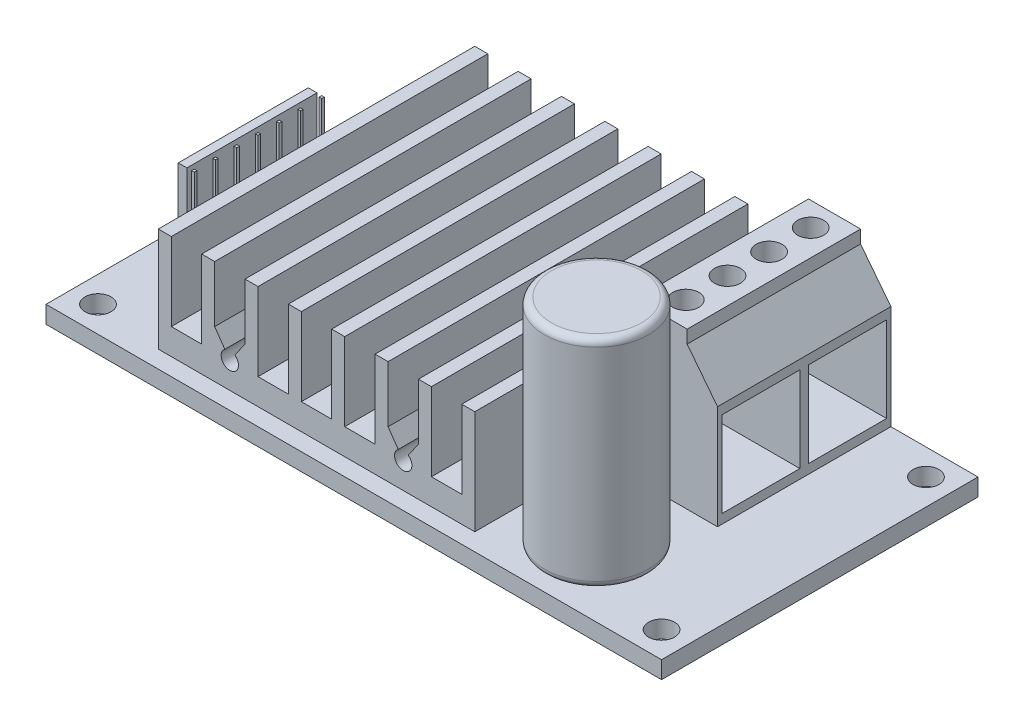
SolidWorks part; units mm, degrees
ref_plane "Front Plane" through (0, 0, 0) normal (0, 0, 1) x (1, 0, 0)
ref_plane "Top Plane" through (0, 0, 0) normal (0, 1, 0) x (1, 0, 0)
ref_plane "Right Plane" through (0, 0, 0) normal (1, 0, 0) x (0, 0, -1)
sketch "Sketch1" plane through (0, 0, 0) normal (0, 1, 0) x (1, 0, 0)
  line L1 (-35.5, -18.25) -> (35.5, -18.25)
  line L2 (-35.5, -18.25) -> (-35.5, 18.25)
  line L3 (-35.5, 18.25) -> (35.5, 18.25)
  line L4 (35.5, -18.25) -> (35.5, 18.25)
  line L5 (-35.5, -18.25) -> (35.5, 18.25) construction
  line L6 (-35.5, 18.25) -> (35.5, -18.25) construction
  point P0 (0, 0)
  dimension "D1" = 71
  dimension "D2" = 36.5
extrude "Board" add sketch "Sketch1" along normal blind 2
sketch "Sketch2" plane through (0, 2, 0) normal (0, 1, 0) x (1, 0, 0)
  line L0 (35.5, 18.25) -> (-35.5, 18.25) construction
  line L1 (-35.5, 18.25) -> (-35.5, -18.25) construction
  line L2 (-35.5, 0) -> (0, 0) construction
  line L3 (0, 0) -> (0, 18.25) construction
  circle A0 centre (-32.5, 15.25) radius 1.5
  circle A1 centre (32.5, 15.25) radius 1.5
  circle A2 centre (32.5, -15.25) radius 1.5
  circle A3 centre (-32.5, -15.25) radius 1.5
  dimension "D1" = 3
  dimension "D2" = 3
  dimension "D3" = 3
extrude "Screw Holes" cut sketch "Sketch2" against normal blind 2
sketch "Sketch3" plane through (0, 0, 18.25) normal (0, 0, 1) x (1, 0, 0)
  line L0 (-35.5, 2) -> (-23.5, 2) construction
  line L1 (-35.5, 2) -> (35.5, 2) construction
  line L2 (-22.5449, 4) -> (13.9551, 4)
  line L3 (-22.5449, 4) -> (-22.5449, 16)
  line L4 (-17.5449, 7) -> (-17.5449, 16)
  line L5 (-12.5449, 9.4993) -> (-12.5449, 16)
  line L6 (-7.5449, 7) -> (-7.5449, 16)
  line L7 (-2.5449, 7) -> (-2.5449, 16)
  line L8 (2.4551, 7) -> (2.4551, 16)
  line L9 (7.4551, 9.4993) -> (7.4551, 16)
  line L10 (12.4551, 7) -> (12.4551, 16)
  line L11 (-21.0449, 7) -> (-21.0449, 16)
  line L12 (-16.0449, 9.4993) -> (-16.0449, 16)
  line L13 (-11.0449, 7) -> (-11.0449, 16)
  line L14 (-6.0449, 7) -> (-6.0449, 16)
  line L15 (-1.0449, 7) -> (-1.0449, 16)
  line L16 (3.9551, 9.4993) -> (3.9551, 16)
  line L17 (8.9551, 7) -> (8.9551, 16)
  line L18 (13.9551, 4) -> (13.9551, 16)
  line L19 (-22.5449, 16) -> (-21.0449, 16)
  line L20 (-17.5449, 16) -> (-16.0449, 16)
  line L21 (-12.5449, 16) -> (-11.0449, 16)
  line L22 (-7.5449, 16) -> (-6.0449, 16)
  line L23 (-2.5449, 16) -> (-1.0449, 16)
  line L24 (2.4551, 16) -> (3.9551, 16)
  line L25 (7.4551, 16) -> (8.9551, 16)
  line L26 (12.4551, 16) -> (13.9551, 16)
  line L27 (-21.0449, 7) -> (-17.5449, 7)
  line L28 (-22.5449, 7) -> (13.9551, 7) construction
  line L29 (-21.0449, 4) -> (-21.0449, 16) construction
  line L30 (8.9551, 7) -> (12.4551, 7)
  line L32 (-1.0449, 7) -> (2.4551, 7)
  line L33 (-6.0449, 7) -> (-2.5449, 7)
  line L34 (-11.0449, 7) -> (-7.5449, 7)
  line L35 (-13.5823, 7) -> (-15.0075, 7)
  line L36 (-14.2949, 7) -> (-14.2949, 8) construction
  line L37 (-13.7213, 7.8192) -> (-12.5449, 9.4993)
  line L38 (-14.8685, 7.8192) -> (-16.0449, 9.4993)
  line L39 (5.7051, 7) -> (5.7051, 8) construction
  line L40 (6.2787, 7.8192) -> (7.4551, 9.4993)
  line L41 (5.1315, 7.8192) -> (3.9551, 9.4993)
  arc A0 (-14.8685, 7.8192) -> (-13.7213, 7.8192) centre (-14.2949, 7) ccw
  arc A1 (5.1315, 7.8192) -> (6.2787, 7.8192) centre (5.7051, 7) ccw
  dimension "D10" = 2
  dimension "D12" = 2
  dimension "D1" = 12
  dimension "D2" = 3
  dimension "D3" = 12
  dimension "D4" = 2
  dimension "D8" = 12
  dimension "D9" = 1.5
  dimension "D11" = 35
  dimension "D13" = 35
  dimension "D6" = 1.5
  dimension "D5" = 8
  dimension "D7" = 8
extrude "Fins" add sketch "Sketch3" against normal blind 36.5 separate body contours A1 L41 L16 L24 L8 L32 L15 L23 L7 L33 L14 L22 L6 L34 L13 L21 L5 L37 A0 L38 L12 L20 L4 L27 L11 L19 L3 L2 L18 L26 L10 L30 L17 L25 L9 L40
sketch "Sketch4" plane through (0, 2, 0) normal (0, 1, 0) x (1, 0, 0)
  line L1 (20.5, 18.25) -> (20.5, -18.25) construction
  line L2 (35.5, 18.25) -> (-35.5, 18.25) construction
  line L3 (-35.5, -18.25) -> (35.5, -18.25) construction
  line L4 (35.5, -18.25) -> (35.5, 18.25) construction
  line L5 (18.3627, -10.75) -> (27.0422, -10.75) construction
  circle A0 centre (20.5, -10.75) radius 6
  dimension "D3" = 12
  dimension "D1" = 15
  dimension "D2" = 7.5
extrude "capacitor" add sketch "Sketch4" along normal blind 25 separate body
fillet "capacitor fillet" radius 0.8 2 edges at (20.5, 2, 16.75) (20.5, 27, 16.75)
sketch "Sketch5" plane through (0, 2, 0) normal (0, 1, 0) x (1, 0, 0)
  line L0 (-35.5, 11.25) -> (35.5, 11.25) construction
  line L1 (-35.5, 18.25) -> (-35.5, -18.25) construction
  line L2 (35.5, -18.25) -> (35.5, 18.25) construction
  line L3 (35.5, 18.25) -> (-35.5, 18.25) construction
  line L4 (-35.5, 0) -> (35.5, 0) construction
  line L5 (-35.5, -11.25) -> (35.5, -11.25) construction
  circle A0 centre (-4.3257, 11.25) radius 1
  circle A1 centre (-4.3257, -11.25) radius 1
  dimension "D2" = 2
  dimension "D1" = 7
extrude "Fin Screw" cut sketch "Sketch5" against normal blind 4 and the other way blind 13
sketch "Sketch7" plane through (0, 7, 0) normal (0, 1, 0) x (1, 0, 0)
  circle A0 centre (-4.3257, -11.25) radius 1 construction
  circle A1 centre (-4.3257, 11.25) radius 1 construction
  circle A2 centre (-4.3257, -11.25) radius 1
  circle A3 centre (-4.3257, 11.25) radius 1
extrude "Fin Screw 2" cut sketch "Sketch7" against normal blind 4
sketch "Sketch8" plane through (0, 2, 0) normal (0, 1, 0) x (1, 0, 0)
  line L0 (-35.5, 0) -> (-25.4782, 0) construction
  line L1 (-35.5, 18.25) -> (-35.5, -18.25) construction
  line L2 (-31, 9) -> (-31, -9)
  line L3 (-25.5, 9) -> (-25.5, -9)
  line L4 (-31, 9) -> (-25.5, 9)
  line L5 (-31, -9) -> (-25.5, -9)
  point P7 (-30.4891, 0)
  point P10 (-31, 0)
  dimension "D1" = 18
  dimension "D2" = 4.5
  dimension "D3" = 5.5
extrude "Pin Base" add sketch "Sketch8" along normal blind 3 separate body
sketch "Sketch9" plane through (0, 5, 0) normal (0, 1, 0) x (1, 0, 0)
  line L0 (-31, 7.5) -> (-31, -7.5)
  line L1 (-31, 9) -> (-31, -9) construction
  line L3 (-30, 7.5) -> (-30, -7.5)
  line L4 (-31, -7.5) -> (-30, -7.5)
  line L5 (-31, 7.5) -> (-30, 7.5)
  point P4 (-31, 0)
  dimension "D1" = 15
  dimension "D2" = 1
extrude "Boss-Extrude6" add sketch "Sketch9" along normal blind 8 separate body
sketch "Sketch10" plane through (0, 5, 0) normal (0, 1, 0) x (1, 0, 0)
  line L0 (-29.3, 9) -> (-29.3, -9) construction
  line L1 (-25.5, 9) -> (-31, 9) construction
  line L2 (-31, -9) -> (-25.5, -9) construction
  line L3 (-31, -7.5) -> (-30, -7.5) construction
  line L4 (-29.45, -7.2) -> (-29.15, -7.2)
  line L5 (-29.45, -7.2) -> (-29.45, -7.5)
  line L6 (-29.45, -7.5) -> (-29.15, -7.5)
  line L7 (-29.15, -7.2) -> (-29.15, -7.5)
  line L8 (-29.45, -7.2) -> (-29.15, -7.5) construction
  line L9 (-29.45, -7.5) -> (-29.15, -7.2) construction
  line L10 (-30, -7.5) -> (-30, 7.5) construction
  line L11 (-29.45, -4.75) -> (-29.45, -5.05)
  line L12 (-29.45, -4.75) -> (-29.15, -4.75)
  line L13 (-29.15, -4.75) -> (-29.15, -5.05)
  line L14 (-29.45, -5.05) -> (-29.15, -5.05)
  line L15 (-29.45, -2.3) -> (-29.45, -2.6)
  line L16 (-29.45, -2.3) -> (-29.15, -2.3)
  line L17 (-29.15, -2.3) -> (-29.15, -2.6)
  line L18 (-29.45, -2.6) -> (-29.15, -2.6)
  line L19 (-29.45, 0.15) -> (-29.45, -0.15)
  line L20 (-29.45, 0.15) -> (-29.15, 0.15)
  line L21 (-29.15, 0.15) -> (-29.15, -0.15)
  line L22 (-29.45, -0.15) -> (-29.15, -0.15)
  line L23 (-29.45, 2.6) -> (-29.45, 2.3)
  line L24 (-29.45, 2.6) -> (-29.15, 2.6)
  line L25 (-29.15, 2.6) -> (-29.15, 2.3)
  line L26 (-29.45, 2.3) -> (-29.15, 2.3)
  line L27 (-29.45, 5.05) -> (-29.45, 4.75)
  line L28 (-29.45, 5.05) -> (-29.15, 5.05)
  line L29 (-29.15, 5.05) -> (-29.15, 4.75)
  line L30 (-29.45, 4.75) -> (-29.15, 4.75)
  line L31 (-29.45, 7.5) -> (-29.45, 7.2)
  line L32 (-29.45, 7.5) -> (-29.15, 7.5)
  line L33 (-29.15, 7.5) -> (-29.15, 7.2)
  line L34 (-29.45, 7.2) -> (-29.15, 7.2)
  point P6 (-29.3, -7.35)
  point P13 (-29.3, -7.5)
  point P16 (-29.45, 0)
  dimension "D1" = 0.3
  dimension "D2" = 0.3
  dimension "D3" = 0.7
  dimension "D4" = 7
extrude "Boss-Extrude7" add sketch "Sketch10" along normal blind 8 separate body
sketch "Sketch11" plane through (0, 0, 0) normal (0, -1, 0) x (1, 0, 0)
  circle A0 centre (-4.3257, -11.25) radius 1 construction
  circle A1 centre (-4.3257, 11.25) radius 1 construction
  circle A2 centre (-4.3257, -11.25) radius 1
  circle A3 centre (-4.3257, 11.25) radius 1
extrude "Boss-Extrude8" add sketch "Sketch11" against normal blind 7 separate body
sketch "Sketch12" plane through (0, 0, -18.25) normal (0, 0, -1) x (-1, 0, 0)
  line L0 (-13.9551, 2) -> (-13.9551, 12)
  line L1 (-35.5, 2) -> (35.5, 2) construction
  line L2 (-13.9551, 4) -> (-13.9551, 16) construction
  line L3 (-13.9551, 12) -> (-15.9551, 12)
  line L4 (-15.9551, 12) -> (-15.9551, 20)
  line L5 (-15.9551, 20) -> (-21.9551, 20)
  line L6 (-21.9551, 20) -> (-21.9551, 18.5)
  line L7 (-13.9551, 2) -> (-25.4551, 2)
  line L8 (-25.4551, 2) -> (-25.4551, 14)
  line L9 (-25.4551, 14) -> (-21.9551, 18.5)
  dimension "D1" = 10
  dimension "D2" = 2
  dimension "D3" = 8
  dimension "D4" = 6
  dimension "D5" = 1.5
  dimension "D6" = 11.5
  dimension "D7" = 12
extrude "Boss-Extrude9" add sketch "Sketch12" against normal blind 20 separate body
sketch "Sketch13" plane through (25.4551, 0, 0) normal (1, 0, 0) x (0, 0, -1)
  line L0 (8.25, 2) -> (8.25, 14) construction
  line L1 (-1.75, 2) -> (18.25, 2) construction
  line L2 (-1.75, 14) -> (18.25, 14) construction
  line L3 (8.25, 8) -> (-1.75, 8) construction
  line L4 (-1.75, 14) -> (-1.75, 2) construction
  line L5 (17.75, 12.9309) -> (8.75, 12.9309)
  line L6 (-1.25, 3.0691) -> (7.75, 3.0691)
  line L7 (-1.25, 3.0691) -> (-1.25, 12.9309)
  line L8 (-1.25, 12.9309) -> (7.75, 12.9309)
  line L9 (7.75, 3.0691) -> (7.75, 12.9309)
  line L10 (-1.25, 3.0691) -> (7.75, 12.9309) construction
  line L11 (-1.25, 12.9309) -> (7.75, 3.0691) construction
  line L12 (8.75, 3.0691) -> (8.75, 12.9309)
  line L13 (17.75, 3.0691) -> (8.75, 3.0691)
  line L14 (17.75, 3.0691) -> (17.75, 12.9309)
  point P10 (3.25, 8)
  dimension "D1" = 0.5
extrude "Cut-Extrude1" cut sketch "Sketch13" against normal blind 9
sketch "Sketch14" plane through (0, 20, 0) normal (0, 1, 0) x (1, 0, 0)
  line L0 (18.9551, 18.25) -> (18.9551, -1.75) construction
  line L1 (15.9551, 18.25) -> (21.9551, 18.25) construction
  line L2 (15.9551, -1.75) -> (21.9551, -1.75) construction
  circle A0 centre (18.9551, 15.4983) radius 1.5
  circle A1 centre (18.9551, 10.6983) radius 1.5
  circle A2 centre (18.9551, 5.8983) radius 1.5
  circle A3 centre (18.9551, 1.0983) radius 1.5
  dimension "D1" = 3
  dimension "D2" = 4
extrude "Cut-Extrude2" cut sketch "Sketch14" against normal blind 9
